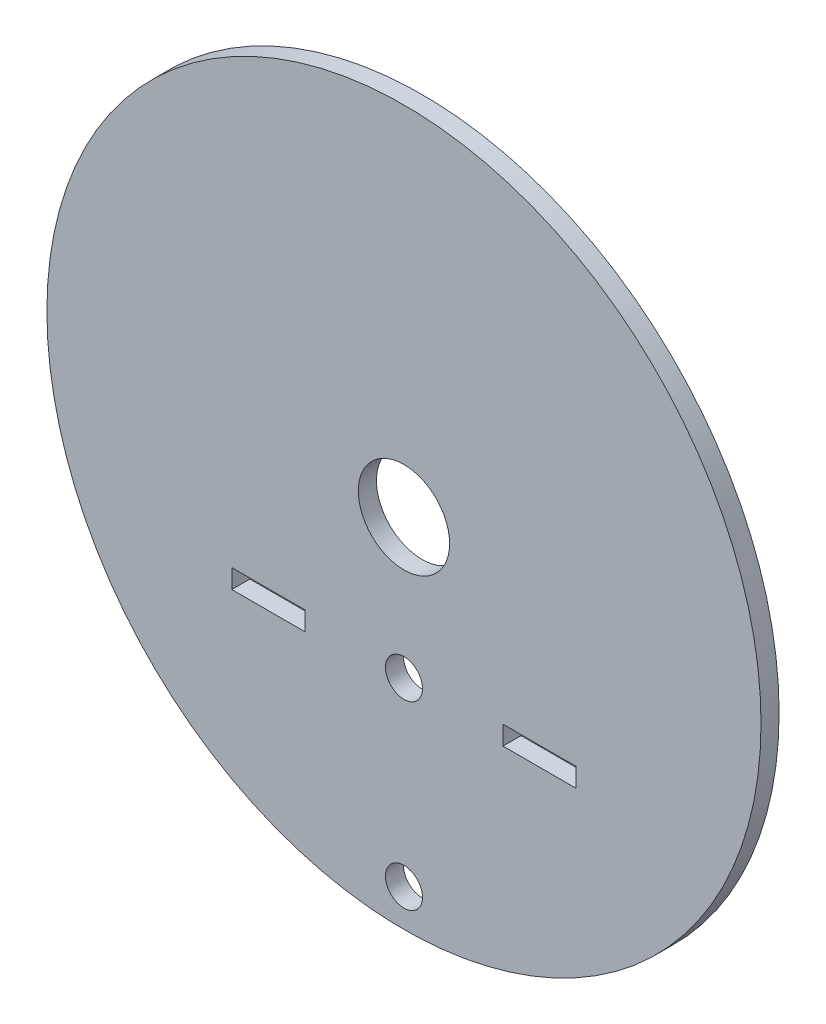
SolidWorks part; units mm, degrees
ref_plane "前视基准面" through (0, 0, 0) normal (0, 0, 1) x (1, 0, 0)
ref_plane "上视基准面" through (0, 0, 0) normal (0, 1, 0) x (1, 0, 0)
ref_plane "右视基准面" through (0, 0, 0) normal (1, 0, 0) x (0, 0, -1)
sketch "草图1" plane through (0, 0, 0) normal (0, 0, 1) x (1, 0, 0)
  line L0 (0, 0) -> (0, 20) construction
  line L1 (0, 20) -> (-15, 20) construction
  line L2 (0, 10) -> (-3.9018, 10) construction
  line L3 (-19.05, 21.05) -> (-10.95, 21.05)
  line L4 (-19.05, 21.05) -> (-19.05, 18.95)
  line L5 (-19.05, 18.95) -> (-10.95, 18.95)
  line L6 (-10.95, 21.05) -> (-10.95, 18.95)
  line L7 (-19.05, 21.05) -> (-10.95, 18.95) construction
  line L8 (-19.05, 18.95) -> (-10.95, 21.05) construction
  line L13 (10.95, 21.05) -> (10.95, 18.95)
  line L14 (19.05, 21.05) -> (10.95, 21.05)
  line L15 (19.05, 21.05) -> (19.05, 18.95)
  line L16 (19.05, 18.95) -> (10.95, 18.95)
  circle A0 centre (0, 0) radius 2.05
  circle A1 centre (0, 20) radius 2.05
  circle A2 centre (0, 35.4) radius 5.05
  circle A4 centre (0, 35.4) radius 12 construction
  circle A6 centre (0, 35.4) radius 39.5
  circle A9 centre (0, 35.4) radius 37.5 construction
  circle A10 centre (0, 20) radius 3.35 construction
  dimension "D1" = 4.1
  dimension "D3" = 4.1
  dimension "D7" = 10.1
  dimension "D9" = 24
  dimension "D10" = 79
  dimension "D11" = 6.7
  dimension "D2" = 20
  dimension "D4" = 15
  dimension "D5" = 8.1
  dimension "D6" = 2.1
  dimension "D8" = 15.4
extrude "凸台-拉伸1" add sketch "草图1" along normal blind 2
